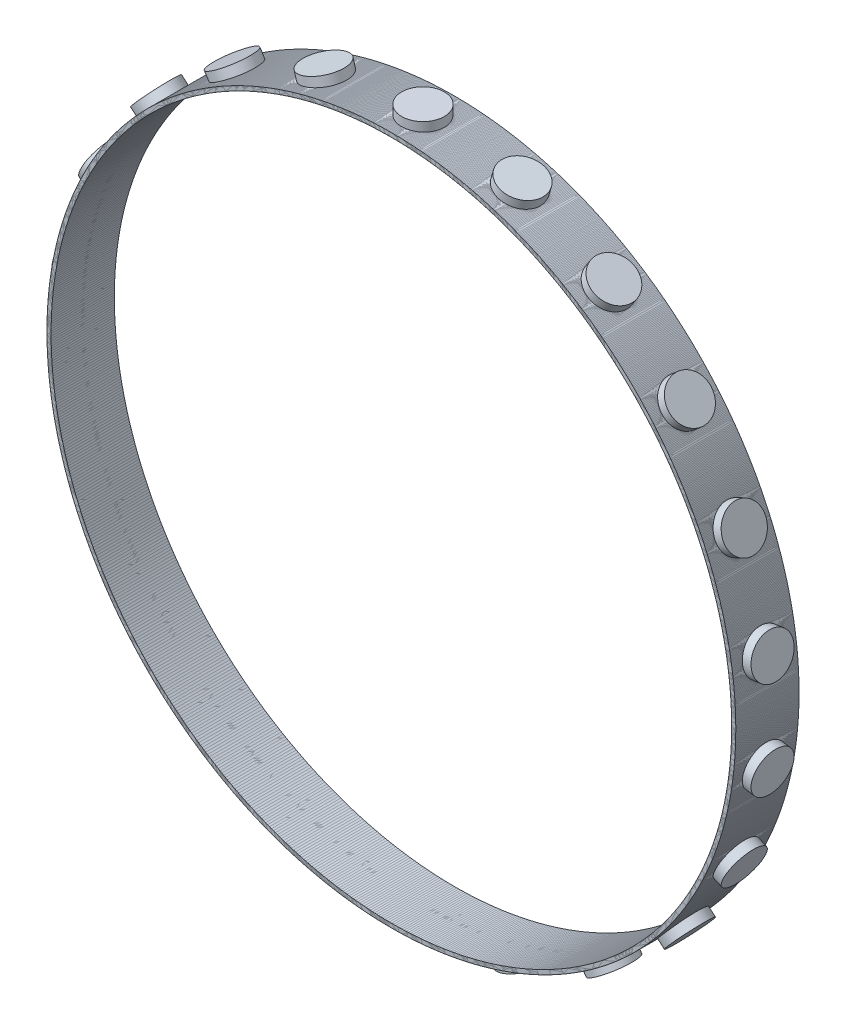
SolidWorks part; units mm, degrees
ref_plane "Front Plane" through (0, 0, 0) normal (0, 0, 1) x (1, 0, 0)
ref_plane "Top Plane" through (0, 0, 0) normal (0, 1, 0) x (1, 0, 0)
ref_plane "Right Plane" through (0, 0, 0) normal (1, 0, 0) x (0, 0, -1)
sketch "Sketch1" plane through (0, 0, 0) normal (0, 0, 1) x (1, 0, 0)
  circle A0 centre (0, 0) radius 54.6735
  circle A1 centre (0, 0) radius 55.3085
  dimension "D1" = 109.347
  dimension "D2" = 0.635
extrude "Boss-Extrude1" add sketch "Sketch1" along normal blind 10.16
sketch "Sketch2" plane through (0, 0, 0) normal (0, 1, 0) x (1, 0, 0)
  line L0 (0, 0) -> (0, -10.16) construction
  line L1 (-55.3085, -10.16) -> (55.3085, -10.16) construction
  circle A0 centre (0, -5.08) radius 3.429
  point P7 (0, -5.08)
  dimension "D1" = 6.858
ref_plane "Plane1" through (0, 54.6862, 0) normal (0, 1, 0) x (1, 0, 0)
extrude "Boss-Extrude2" add sketch "Sketch2" along normal blind 2.032 from surface at 54.6862 contours A0 starting at plane "Plane1"
pattern_circular "CirPattern2" count 22 over 360 about axis through (0, 0, 0) along (0, 0, 1) of bodies 102
